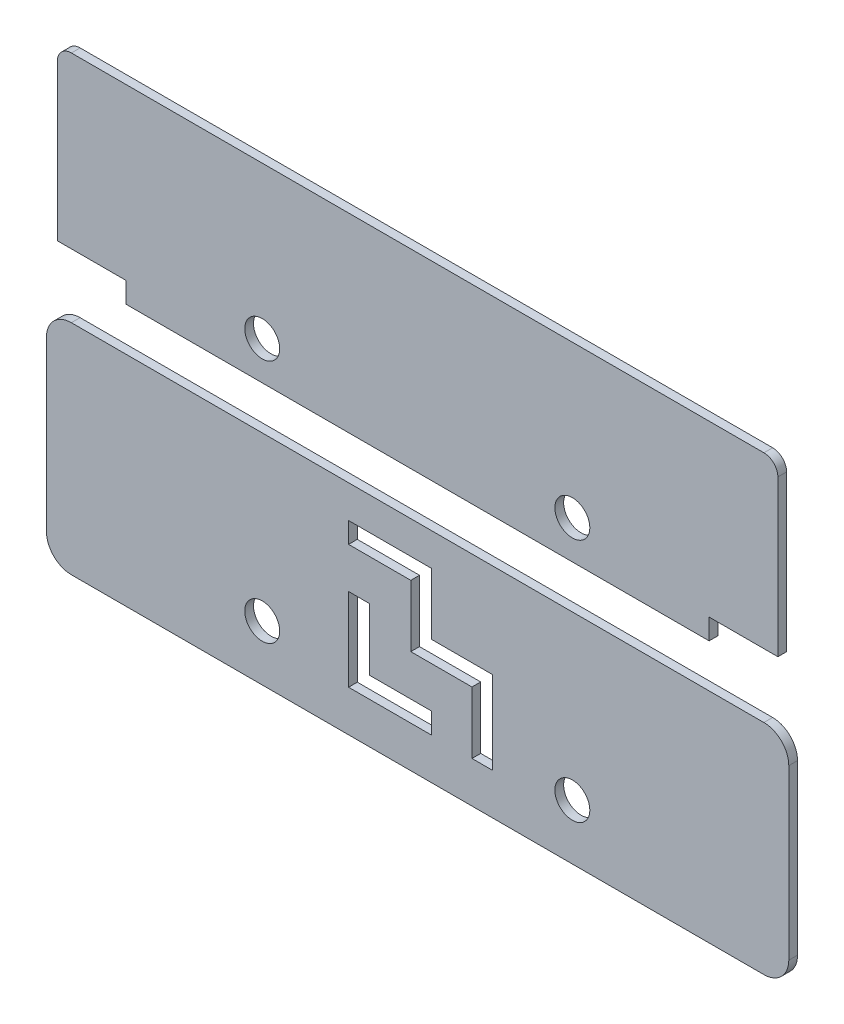
SolidWorks part; units mm, degrees
ref_plane "Front" through (0, 0, 0) normal (0, 0, 1) x (1, 0, 0)
ref_plane "Top" through (0, 0, 0) normal (0, 1, 0) x (1, 0, 0)
ref_plane "Right" through (0, 0, 0) normal (1, 0, 0) x (0, 0, -1)
sketch "Sketch1" plane through (0, 0, 0) normal (0, 0, 1) x (1, 0, 0)
  line L0 (-52.6295, -31.75) -> (-37.7705, -31.75)
  line L1 (37.5705, -31.75) -> (52.4295, -31.75)
  line L2 (-107.95, 24.511) -> (-107.95, -24.511)
  line L3 (-100.711, -31.75) -> (-52.6295, -31.75)
  line L4 (-37.7705, -31.75) -> (37.5705, -31.75)
  line L5 (52.4295, -31.75) -> (100.711, -31.75)
  line L6 (107.95, -24.511) -> (107.95, 24.511)
  line L7 (100.711, 31.75) -> (-100.711, 31.75)
  line L24 (100.711, 99.695) -> (-100.711, 99.695)
  line L25 (-104.775, 95.631) -> (-104.775, 50.345)
  line L31 (104.775, 50.345) -> (104.775, 95.631)
  line L32 (107.95, 46.609) -> (107.95, 95.631) [skipped]
  line L33 (84.775, 44.345) -> (-84.775, 44.345)
  line L34 (100.711, 102.87) -> (-100.711, 102.87) [skipped]
  line L35 (84.775, 44.345) -> (84.775, 50.345)
  line L36 (52.4295, 39.37) -> (100.711, 39.37) [skipped]
  line L37 (84.775, 50.345) -> (104.775, 50.345)
  line L38 (37.5705, 39.37) -> (52.4295, 39.37) [skipped]
  line L40 (-37.7705, 39.37) -> (37.5705, 39.37) [skipped]
  line L41 (0, 99.695) -> (0, 44.345) construction
  line L42 (-52.6295, 39.37) -> (-37.7705, 39.37) [skipped]
  line L43 (-84.775, 50.345) -> (-104.775, 50.345)
  line L44 (-100.711, 39.37) -> (-52.6295, 39.37) [skipped]
  line L45 (-84.775, 44.345) -> (-84.775, 50.345)
  line L46 (-107.95, 95.631) -> (-107.95, 46.609) [skipped]
  circle A0 centre (-45.2, -15.6502) radius 5.08
  circle A1 centre (45, -15.6502) radius 5.08
  arc A2 (-100.711, 31.75) -> (-107.95, 24.511) centre (-100.711, 24.511) ccw
  arc A3 (-107.95, -24.511) -> (-100.711, -31.75) centre (-100.711, -24.511) ccw
  arc A4 (100.711, -31.75) -> (107.95, -24.511) centre (100.711, -24.511) ccw
  arc A5 (107.95, 24.511) -> (100.711, 31.75) centre (100.711, 24.511) ccw
  circle A10 centre (-45.2, 55.4698) radius 5.08
  circle A11 centre (45, 55.4698) radius 5.08
  arc A18 (-100.711, 99.695) -> (-104.775, 95.631) centre (-100.711, 95.631) ccw
  arc A21 (104.775, 95.631) -> (100.711, 99.695) centre (100.711, 95.631) ccw
  arc A24 (107.95, 95.631) -> (100.711, 102.87) centre (100.711, 95.631) ccw [skipped]
  circle A25 centre (66.273, 2.3) radius 1.905 construction
  arc A26 (100.711, 39.37) -> (107.95, 46.609) centre (100.711, 46.609) ccw [skipped]
  arc A28 (-107.95, 46.609) -> (-100.711, 39.37) centre (-100.711, 46.609) ccw [skipped]
  circle A29 centre (35.023, 2.3) radius 1.905 construction
  arc A30 (-100.711, 102.87) -> (-107.95, 95.631) centre (-100.711, 95.631) ccw [skipped]
  circle A32 centre (50.648, 2.3) radius 12.065 construction
  circle A34 centre (12.5, 2.3) radius 9.25 construction
  dimension "D3" = 2
extrude "Boss-Extrude1" add sketch "Sketch1" along normal blind 2.54
sketch "Sketch2" plane through (0, 0, 2.54) normal (0, 0, 1) x (1, 0, 0)
  line L0 (-20.0864, 22.2366) -> (3.9841, 22.2366)
  line L1 (3.9841, 22.2366) -> (3.9841, 4.3544)
  line L2 (3.9841, 4.3544) -> (21.8236, 4.3544)
  line L3 (21.8236, 4.3544) -> (21.8236, -19.7588)
  line L4 (21.8236, -19.7588) -> (15.806, -19.7588)
  line L5 (15.806, -19.7588) -> (15.806, -1.7486)
  line L6 (15.806, -1.7486) -> (-1.9908, -1.7486)
  line L7 (-1.9908, -1.7486) -> (-1.9908, 16.2189)
  line L8 (-1.9908, 16.2189) -> (-20.0864, 16.2189)
  line L9 (-20.0864, 16.2189) -> (-20.0864, 22.2366)
  line L10 (-20.0864, 4.3544) -> (-14.0261, 4.3544)
  line L11 (-14.0261, 4.3544) -> (-14.0261, -13.6985)
  line L12 (-14.0261, -13.6985) -> (3.9841, -13.6985)
  line L13 (3.9841, -13.6985) -> (3.9841, -19.7588)
  line L14 (3.9841, -19.7588) -> (-20.0864, -19.7588)
  line L15 (-20.0864, -19.7588) -> (-20.0864, 4.3544)
extrude "Cut-Extrude1" cut sketch "Sketch2" against normal through all
sketch "Sketch3" [suppressed] plane through (0, 0, 2.54) normal (0, 0, 1) x (1, 0, 0)
  circle A0 centre (-45.2, 55.4698) radius 5.08 construction
  circle A1 centre (-45.2, 55.4698) radius 5.08
  circle A2 centre (45, 55.4698) radius 5.08 construction
  circle A3 centre (45, 55.4698) radius 5.08
extrude "Boss-Extrude2" [suppressed] add sketch "Sketch3" against normal through all
sketch "Sketch5" [suppressed] plane through (0, 0, 2.54) normal (0, 0, 1) x (1, 0, 0)
  line L0 (3.9841, -19.7588) -> (3.9841, -13.6985) construction
  line L1 (-20.0864, -19.7588) -> (3.9841, -19.7588) construction
  line L2 (-20.0864, 4.3544) -> (-20.0864, -19.7588) construction
  line L3 (-14.0261, 4.3544) -> (-20.0864, 4.3544) construction
  line L4 (-14.0261, -13.6985) -> (-14.0261, 4.3544) construction
  line L5 (3.9841, -13.6985) -> (-14.0261, -13.6985) construction
  line L6 (3.9841, -19.7588) -> (3.9841, -13.6985)
  line L7 (-20.0864, -19.7588) -> (3.9841, -19.7588)
  line L8 (-20.0864, 4.3544) -> (-20.0864, -19.7588)
  line L9 (-14.0261, 4.3544) -> (-20.0864, 4.3544)
  line L10 (-14.0261, -13.6985) -> (-14.0261, 4.3544)
  line L11 (3.9841, -13.6985) -> (-14.0261, -13.6985)
  line L12 (-1.9908, -1.7486) -> (15.806, -1.7486) construction
  line L13 (-1.9908, 16.2189) -> (-1.9908, -1.7486) construction
  line L14 (-20.0864, 16.2189) -> (-1.9908, 16.2189) construction
  line L15 (-20.0864, 22.2366) -> (-20.0864, 16.2189) construction
  line L16 (3.9841, 22.2366) -> (-20.0864, 22.2366) construction
  line L17 (3.9841, 4.3544) -> (3.9841, 22.2366) construction
  line L18 (21.8236, 4.3544) -> (3.9841, 4.3544) construction
  line L19 (21.8236, -19.7588) -> (21.8236, 4.3544) construction
  line L20 (15.806, -19.7588) -> (21.8236, -19.7588) construction
  line L21 (15.806, -1.7486) -> (15.806, -19.7588) construction
  line L22 (-1.9908, -1.7486) -> (15.806, -1.7486)
  line L23 (-1.9908, 16.2189) -> (-1.9908, -1.7486)
  line L24 (-20.0864, 16.2189) -> (-1.9908, 16.2189)
  line L25 (-20.0864, 22.2366) -> (-20.0864, 16.2189)
  line L26 (3.9841, 22.2366) -> (-20.0864, 22.2366)
  line L27 (3.9841, 4.3544) -> (3.9841, 22.2366)
  line L28 (21.8236, 4.3544) -> (3.9841, 4.3544)
  line L29 (21.8236, -19.7588) -> (21.8236, 4.3544)
  line L30 (15.806, -19.7588) -> (21.8236, -19.7588)
  line L31 (15.806, -1.7486) -> (15.806, -19.7588)
  circle A0 centre (-45.2, -15.6502) radius 5.08 construction
  circle A1 centre (-45.2, -15.6502) radius 5.08
  circle A2 centre (45, -15.6502) radius 5.08 construction
  circle A3 centre (45, -15.6502) radius 5.08
extrude "Boss-Extrude3" [suppressed] add sketch "Sketch5" against normal through all
sketch "Sketch6" [suppressed] plane through (0, 0, 2.54) normal (0, 0, 1) x (1, 0, 0)
  circle A0 centre (12.5, 2.3) radius 9.25 construction
  circle A1 centre (12.5, 2.3) radius 9.25
  circle A2 centre (35.023, 2.3) radius 1.905 construction
  circle A3 centre (35.023, 2.3) radius 1.905
  circle A4 centre (50.648, 2.3) radius 12.065 construction
  circle A5 centre (50.648, 2.3) radius 12.065
  circle A6 centre (66.273, 2.3) radius 1.905 construction
  circle A7 centre (66.273, 2.3) radius 1.905
extrude "Cut-Extrude2" [suppressed] cut sketch "Sketch6" against normal through all
sketch "Sketch7" [suppressed] plane through (0, 0, 0) normal (0, 0, -1) x (-1, 0, 0)
  line L1 (-74.2733, 90.9286) -> (5.6813, 90.9286)
  line L2 (-74.2733, 90.9286) -> (-74.2733, 56.2734)
  line L3 (-74.2733, 56.2734) -> (5.6813, 56.2734)
  line L4 (5.6813, 90.9286) -> (5.6813, 56.2734)
extrude "Cut-Extrude3" [suppressed] cut sketch "Sketch7" against normal through all
